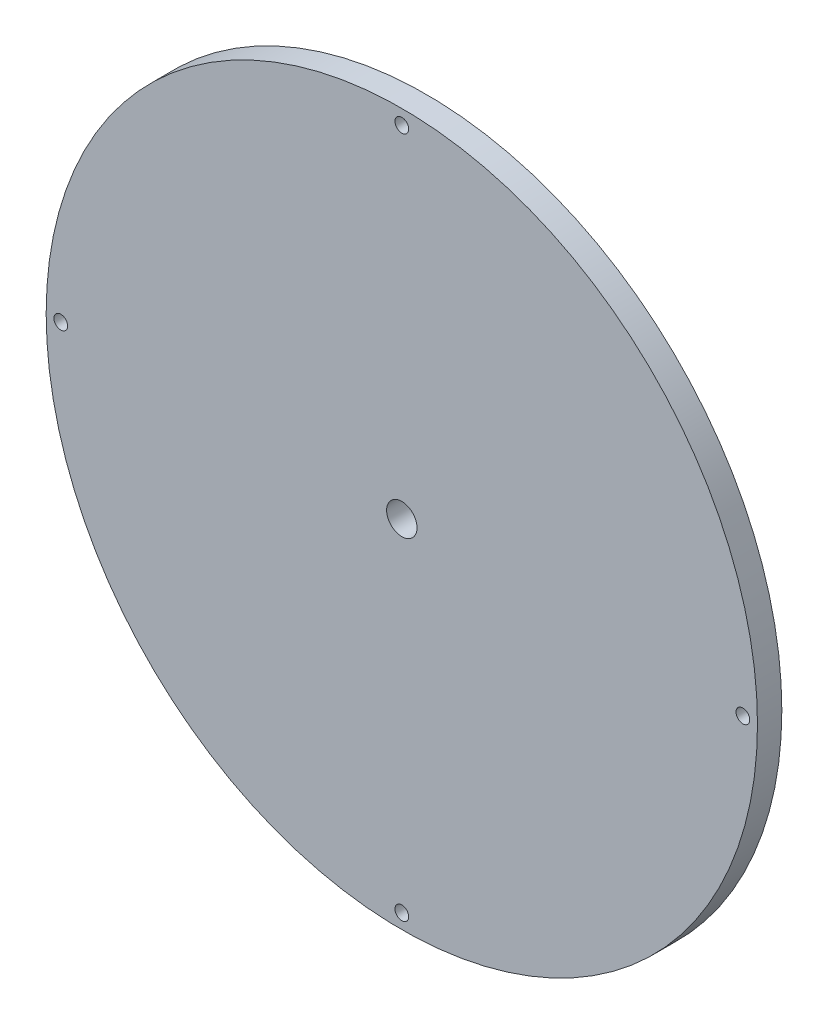
SolidWorks part; units mm, degrees
ref_plane "Front Plane" through (0, 0, 0) normal (0, 0, 1) x (1, 0, 0)
ref_plane "Top Plane" through (0, 0, 0) normal (0, 1, 0) x (1, 0, 0)
ref_plane "Right Plane" through (0, 0, 0) normal (1, 0, 0) x (0, 0, -1)
sketch "Sketch1" plane through (0, 0, 0) normal (0, 0, 1) x (1, 0, 0)
  line L0 (0, 88.9) -> (0, 0) construction
  line L1 (-88.9, 0) -> (0, 0) construction
  circle A0 centre (0, 0) radius 92.71
  circle A5 centre (0, 0) radius 3.9688
  circle A6 centre (0, 88.9) radius 1.7859
  circle A7 centre (88.9, 0) radius 1.7859
  circle A8 centre (0, -88.9) radius 1.7859
  circle A9 centre (-88.9, 0) radius 1.7859
  point P14 (0, 0)
  point P16 (0, 0)
  dimension "D1" = 185.42
  dimension "D2" = 7.9375
  dimension "D3" = 3.5719
  dimension "D5" = 4
  dimension "D4" = 88.9
  dimension "D6" = 88.9
extrude "Boss-Extrude1" add sketch "Sketch1" along normal blind 6.35
